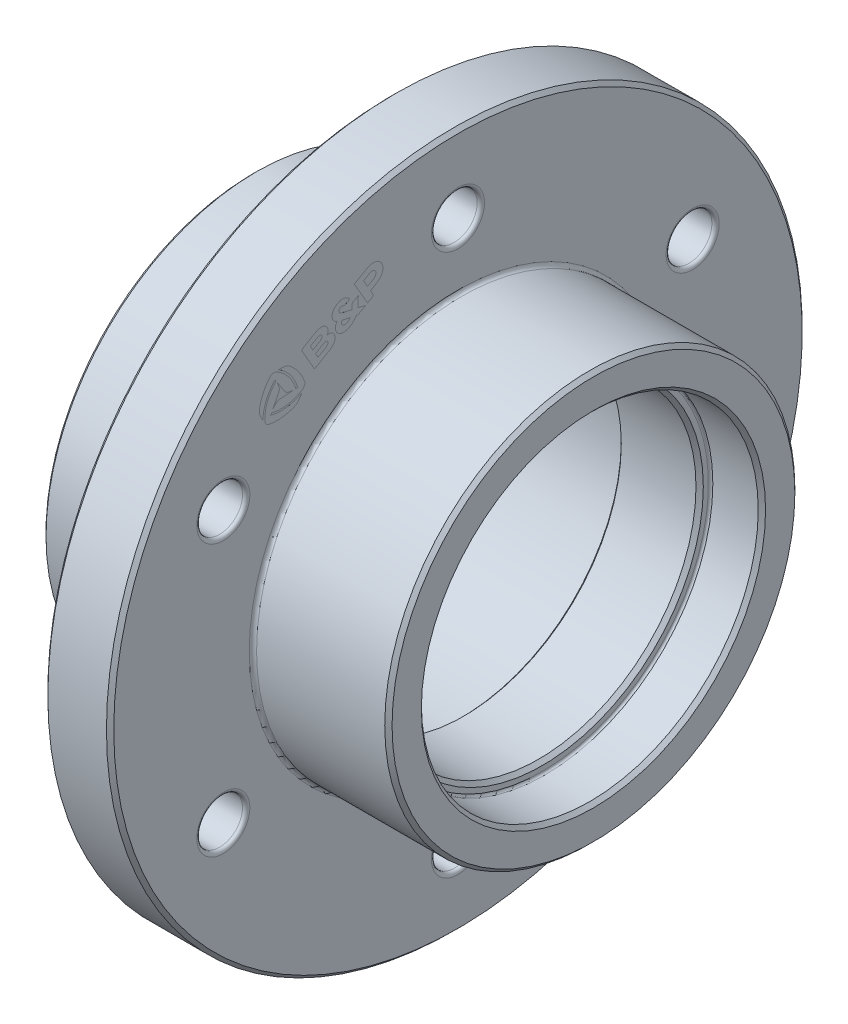
SolidWorks part; units mm, degrees
ref_plane "Alzado" through (0, 0, 0) normal (0, 0, 1) x (1, 0, 0)
ref_plane "Planta" through (0, 0, 0) normal (0, 1, 0) x (1, 0, 0)
ref_plane "Vista lateral" through (0, 0, 0) normal (1, 0, 0) x (0, 0, -1)
sketch "Croquis1" plane through (0, 0, 0) normal (0, 0, 1) x (1, 0, 0)
  line L0 (0, 0) -> (56.1633, 0) construction
  line L1 (0, 23.5) -> (0, 28.75)
  line L2 (0, 28.75) -> (7.75, 28.75)
  line L3 (8, 29) -> (18, 29)
  line L4 (19, 30) -> (19, 47.5)
  line L5 (19, 47.5) -> (28, 47.5)
  line L6 (28, 47.5) -> (28, 28.5)
  line L7 (28.5, 28) -> (46.5, 28)
  line L8 (46.5, 28) -> (46.5, 23.5)
  line L9 (0, 23.5) -> (4.6, 23.5)
  line L10 (4.6, 23.5) -> (4.6, 24.75)
  line L11 (4.6, 24.75) -> (6.7, 24.75)
  line L12 (6.7, 24.75) -> (6.7, 23.5)
  line L13 (6.7, 23.5) -> (27.5, 23.5)
  line L20 (28.5, 22.5) -> (28.5, 21.5)
  line L21 (28.5, 21.5) -> (39, 21.5)
  line L22 (8, 29) -> (7.75, 28.75)
  line L23 (46, 23) -> (39.8, 23)
  line L24 (39.5, 22.7) -> (39.5, 22)
  line L25 (46.5, 23.5) -> (46, 23)
  line L26 (39.5, 22) -> (39, 21.5)
  arc A5 (19, 30) -> (18, 29) centre (18, 30) cw
  arc A8 (27.5, 23.5) -> (28.5, 22.5) centre (27.5, 22.5) cw
  arc A9 (28, 28.5) -> (28.5, 28) centre (28.5, 28.5) ccw
  arc A10 (39.8, 23) -> (39.5, 22.7) centre (39.8, 22.7) ccw
  point P6 (46.5, 23)
  point P14 (39.5, 21.5)
  dimension "D7" = 23.5
  dimension "D5" = 1
  dimension "D8" = 8
  dimension "D11" = 57.5
  dimension "D13" = 0.5
  dimension "D18" = 43
  dimension "D16" = 1
  dimension "D22" = 0.3
  dimension "D2" = 19
  dimension "D3" = 28
  dimension "D4" = 46.5
  dimension "D6" = 58
  dimension "D9" = 47.5
  dimension "D10" = 28
  dimension "D12" = 24.75
  dimension "D14" = 2.1
  dimension "D15" = 21.8
  dimension "D17" = 18
  dimension "D19" = 7
  dimension "D20" = 45
  dimension "D21" = 46
revolve "Revolución1" add sketch "Croquis1" angle 360 about L0
sketch "Croquis2" plane through (0, 0, 0) normal (1, 0, 0) x (0, 0, -1)
  line L0 (0, 0) -> (0, 37) construction
  circle A0 centre (0, 0) radius 37 construction
  circle A1 centre (0, 37) radius 3.125
  circle A2 centre (32.0429, 18.5) radius 3.125
  circle A3 centre (32.0429, -18.5) radius 3.125
  circle A4 centre (0, -37) radius 3.125
  circle A5 centre (-32.0429, -18.5) radius 3.125
  circle A6 centre (-32.0429, 18.5) radius 3.125
  point P18 (0, 0)
  dimension "D1" = 6.25
  dimension "D2" = 74
  dimension "D3" = 6
extrude "Cortar-Extruir2" cut sketch "Croquis2" along normal through all
chamfer "Chaflán1" distance 0.5 angle 45 4 edges at (28, 0, 47.5) (19, 0, 47.5) (46.5, 0, 28) (0, 0, 28.75)
fillet "Redondeo2" radius 0.5 12 edges at (19, 18.5, -35.1679) (28, 18.5, -28.9179) (19, -18.5, -35.1679) (28, -18.5, -28.9179) (19, -37, -3.125) (28, -37, 3.125) (19, -18.5, 28.9179) (28, -18.5, 35.1679) (19, 18.5, 28.9179) (28, 18.5, 35.1679) (19, 37, -3.125) (28, 37, 3.125)
chamfer "Chaflán2" distance 0.3 angle 45 1 edges at (28.5, 0, 21.5)
chamfer "Chaflán3" distance 1 angle 45 1 edges at (0, 0, 23.5)
sketch "Croquis3" plane through (28, 0, 0) normal (1, 0, 0) x (0, 0, -1)
  line L0 (0, 0) -> (0, 37) construction
  line L1 (0, 0) -> (-32.0429, 18.5) construction
  line L2 (-12.5294, 37.1945) -> (-14.1517, 36.2579)
  line L3 (-14.1517, 36.2579) -> (-12.3456, 33.1298)
  line L4 (-12.3456, 33.1298) -> (-11.7225, 33.4895)
  line L5 (-11.6274, 33.8445) -> (-11.9408, 34.3873)
  line L6 (-11.9408, 34.3873) -> (-11.2369, 34.7937)
  line L7 (-11.5941, 35.5282) -> (-12.3482, 35.0929)
  line L8 (-12.3482, 35.0929) -> (-12.8933, 36.0372)
  line L9 (-12.8933, 36.0372) -> (-12.1393, 36.4725)
  line L10 (-13.6737, 33.2278) -> (-13.6701, 33.2681)
  line L11 (-13.6701, 33.2681) -> (-13.609, 34.6574)
  line L12 (-13.609, 34.6574) -> (-14.3198, 34.247)
  line L13 (-14.4494, 34.0353) -> (-14.4814, 33.4099)
  line L14 (-14.4814, 33.4099) -> (-15.3436, 33.6051)
  line L15 (-15.4143, 34.4672) -> (-14.7923, 34.8263)
  line L16 (-14.7923, 34.8263) -> (-14.8004, 34.8363)
  line L17 (-13.886, 32.425) -> (-13.7462, 32.3965)
  line L18 (-13.5644, 32.4261) -> (-12.5979, 32.9841)
  line L19 (-12.5979, 32.9841) -> (-13.6737, 33.2278)
  line L20 (-15.8109, 32.8267) -> (-14.7061, 32.5936)
  line L21 (-19.5117, 33.1633) -> (-21.1631, 32.2098)
  line L22 (-21.2582, 31.8549) -> (-19.5821, 28.9518)
  line L23 (-19.5821, 28.9518) -> (-17.6053, 30.0931)
  line L24 (-18.9126, 31.8242) -> (-19.8104, 31.3059)
  line L25 (-19.8104, 31.3059) -> (-20.1601, 31.9117)
  line L26 (-20.1601, 31.9117) -> (-19.2623, 32.43)
  line L27 (-18.1011, 30.6968) -> (-19.1193, 30.109)
  line L28 (-19.1193, 30.109) -> (-19.4552, 30.6909)
  line L29 (-19.4552, 30.6909) -> (-18.422, 31.2874)
  line L30 (-21.8943, 27.9067) -> (-22.1419, 27.8926)
  line L31 (-24.9798, 30.3675) -> (-24.8439, 30.1601)
  line L32 (-25.5683, 26.4649) -> (-25.4565, 26.6866)
  line L33 (-24.8923, 27.473) -> (-25.3244, 26.9485)
  line L34 (-25.3244, 26.9485) -> (-24.4807, 28.6211)
  line L35 (-24.4449, 29.2781) -> (-24.683, 29.9146)
  line L36 (-24.683, 29.9146) -> (-23.6563, 28.3476)
  line L37 (-23.1053, 27.9881) -> (-22.435, 27.8761)
  line L38 (-22.435, 27.8761) -> (-24.3054, 27.7704)
  arc A0 (0, 37) -> (-32.0429, 18.5) centre (0, 0) ccw construction
  spline S0 degree 3 poles (-10.9375, 37.3698) (-11.1564, 37.4796) (-11.4054, 37.5209) (-11.6776, 37.4924) knots 1 1 1 1 2 2 2 2
  spline S1 degree 3 poles (-11.6776, 37.4924) (-11.9499, 37.4639) (-12.2365, 37.3636) (-12.5294, 37.1945) knots 2 2 2 2 3 3 3 3
  spline S2 degree 3 poles (-11.7225, 33.4895) (-11.5984, 33.5612) (-11.5557, 33.7204) (-11.6274, 33.8445) knots 6 6 6 6 7 7 7 7
  spline S3 degree 3 poles (-11.2369, 34.7937) (-10.9305, 34.9706) (-10.6887, 35.1776) (-10.5181, 35.4089) knots 9 9 9 9 10 10 10 10
  spline S4 degree 3 poles (-10.5181, 35.4089) (-10.3475, 35.6402) (-10.2531, 35.8862) (-10.2375, 36.1399) knots 10 10 10 10 11 11 11 11
  spline S5 degree 3 poles (-10.2375, 36.1399) (-10.2299, 36.2639) (-10.2632, 36.6055) (-10.4151, 36.8699) knots 11 11 11 11 12 12 12 12
  spline S6 degree 3 poles (-10.4151, 36.8699) (-10.5716, 37.1423) (-10.8517, 37.3267) (-10.9375, 37.3698) knots 12 12 12 12 13 13 13 13
  spline S7 degree 3 poles (-11.2131, 36.2509) (-11.1849, 36.1445) (-11.1897, 36.0368) (-11.2276, 35.9306) knots 0 0 0 0 1 1 1 1
  spline S8 degree 3 poles (-11.2276, 35.9306) (-11.2844, 35.7712) (-11.4077, 35.6359) (-11.5941, 35.5282) knots 1 1 1 1 2 2 2 2
  spline S9 degree 3 poles (-12.1393, 36.4725) (-11.9529, 36.5802) (-11.7768, 36.6241) (-11.6158, 36.6031) knots 5 5 5 5 6 6 6 6
  spline S10 degree 3 poles (-11.6158, 36.6031) (-11.5124, 36.5896) (-11.4235, 36.5496) (-11.3514, 36.4841) knots 6 6 6 6 7 7 7 7
  spline S11 degree 3 poles (-11.3514, 36.4841) (-11.2855, 36.4243) (-11.2377, 36.3436) (-11.2131, 36.2509) knots 7 7 7 7 8 8 8 8
  spline S12 degree 3 poles (-14.3198, 34.247) (-14.3964, 34.2028) (-14.4448, 34.1236) (-14.4494, 34.0353) knots 3 3 3 3 4 4 4 4
  spline S13 degree 3 poles (-15.3436, 33.6051) (-15.6339, 33.6695) (-15.8393, 33.723) (-15.9541, 33.7643) knots 6 6 6 6 7 7 7 7
  spline S14 degree 3 poles (-15.9541, 33.7643) (-16.069, 33.8056) (-16.1531, 33.8714) (-16.2043, 33.96) knots 7 7 7 7 8 8 8 8
  spline S15 degree 3 poles (-16.2043, 33.96) (-16.2573, 34.0518) (-16.2691, 34.1444) (-16.2394, 34.2353) knots 8 8 8 8 9 9 9 9
  spline S16 degree 3 poles (-16.2394, 34.2353) (-16.2098, 34.3263) (-16.1475, 34.3997) (-16.0543, 34.4535) knots 9 9 9 9 10 10 10 10
  spline S17 degree 3 poles (-16.0543, 34.4535) (-15.9578, 34.5093) (-15.8581, 34.524) (-15.7583, 34.4973) knots 10 10 10 10 11 11 11 11
  spline S18 degree 3 poles (-15.7583, 34.4973) (-15.7286, 34.4893) (-15.6994, 34.4773) (-15.6714, 34.4617) knots 11 11 11 11 12 12 12 12
  spline S19 degree 3 poles (-15.6714, 34.4617) (-15.5938, 34.4184) (-15.4952, 34.4205) (-15.4143, 34.4672) knots 12 12 12 12 13 13 13 13
  spline S20 degree 3 poles (-14.8004, 34.8363) (-14.9946, 35.0763) (-15.2293, 35.2278) (-15.4979, 35.2865) knots 15 15 15 15 16 16 16 16
  spline S21 degree 3 poles (-15.4979, 35.2865) (-15.8028, 35.353) (-16.1262, 35.2893) (-16.4592, 35.097) knots 16 16 16 16 17 17 17 17
  spline S22 degree 3 poles (-16.4592, 35.097) (-16.6856, 34.9663) (-16.8628, 34.8073) (-16.986, 34.6244) knots 17 17 17 17 18 18 18 18
  spline S23 degree 3 poles (-16.986, 34.6244) (-17.1091, 34.4415) (-17.178, 34.2488) (-17.1907, 34.0517) knots 18 18 18 18 19 19 19 19
  spline S24 degree 3 poles (-17.1907, 34.0517) (-17.2034, 33.8545) (-17.1589, 33.6663) (-17.0585, 33.4923) knots 19 19 19 19 20 20 20 20
  spline S25 degree 3 poles (-17.0585, 33.4923) (-16.9488, 33.3024) (-16.7694, 33.1514) (-16.5252, 33.0437) knots 20 20 20 20 21 21 21 21
  spline S26 degree 3 poles (-16.5252, 33.0437) (-16.6487, 32.8499) (-16.722, 32.6493) (-16.743, 32.4475) knots 21 21 21 21 22 22 22 22
  spline S27 degree 3 poles (-16.743, 32.4475) (-16.7641, 32.2456) (-16.7192, 32.0469) (-16.6096, 31.857) knots 22 22 22 22 23 23 23 23
  spline S28 degree 3 poles (-16.6096, 31.857) (-16.4944, 31.6576) (-16.3371, 31.5099) (-16.142, 31.4181) knots 23 23 23 23 24 24 24 24
  spline S29 degree 3 poles (-16.142, 31.4181) (-15.9469, 31.3262) (-15.7233, 31.2938) (-15.4775, 31.3218) knots 24 24 24 24 25 25 25 25
  spline S30 degree 3 poles (-15.4775, 31.3218) (-15.2317, 31.3499) (-14.9771, 31.4391) (-14.7206, 31.5872) knots 25 25 25 25 26 26 26 26
  spline S31 degree 3 poles (-14.7206, 31.5872) (-14.3376, 31.8084) (-14.0568, 32.0902) (-13.886, 32.425) knots 26 26 26 26 27 27 27 27
  spline S32 degree 3 poles (-13.7462, 32.3965) (-13.684, 32.3838) (-13.6194, 32.3944) (-13.5644, 32.4261) knots 29 29 29 29 30 30 30 30
  spline S33 degree 3 poles (-14.7061, 32.5936) (-14.8076, 32.4464) (-14.9317, 32.3299) (-15.0749, 32.2472) knots 0 0 0 0 1 1 1 1
  spline S34 degree 3 poles (-15.0749, 32.2472) (-15.2248, 32.1606) (-15.3767, 32.1254) (-15.5263, 32.1424) knots 1 1 1 1 2 2 2 2
  spline S35 degree 3 poles (-15.5263, 32.1424) (-15.6759, 32.1593) (-15.7842, 32.224) (-15.8482, 32.3348) knots 2 2 2 2 3 3 3 3
  spline S36 degree 3 poles (-15.8482, 32.3348) (-15.8902, 32.4075) (-15.9071, 32.4876) (-15.8985, 32.5727) knots 3 3 3 3 4 4 4 4
  spline S37 degree 3 poles (-15.8985, 32.5727) (-15.89, 32.6578) (-15.8605, 32.7432) (-15.8109, 32.8267) knots 4 4 4 4 5 5 5 5
  spline S38 degree 3 poles (-16.9705, 31.806) (-17.0605, 31.9247) (-17.176, 32.0142) (-17.314, 32.0721) knots 0 0 0 0 1 1 1 1
  spline S39 degree 3 poles (-17.314, 32.0721) (-17.4812, 32.1422) (-17.6811, 32.1426) (-17.8923, 32.0732) knots 1 1 1 1 2 2 2 2
  spline S40 degree 3 poles (-17.8923, 32.0732) (-17.6579, 32.4176) (-17.6726, 32.6513) (-17.839, 32.9783) knots 2 2 2 2 3 3 3 3
  spline S41 degree 3 poles (-17.839, 32.9783) (-17.9924, 33.244) (-18.2198, 33.3961) (-18.5149, 33.4304) knots 3 3 3 3 4 4 4 4
  spline S42 degree 3 poles (-18.5149, 33.4304) (-18.8101, 33.4646) (-19.1455, 33.3747) (-19.5117, 33.1633) knots 4 4 4 4 5 5 5 5
  spline S43 degree 3 poles (-21.1631, 32.2098) (-21.2872, 32.1382) (-21.3299, 31.979) (-21.2582, 31.8549) knots 6 6 6 6 7 7 7 7
  spline S44 degree 3 poles (-17.6053, 30.0931) (-17.2289, 30.3103) (-16.9753, 30.567) (-16.8512, 30.8559) knots 9 9 9 9 10 10 10 10
  spline S45 degree 3 poles (-16.8512, 30.8559) (-16.7271, 31.1448) (-16.7439, 31.4292) (-16.901, 31.7012) knots 10 10 10 10 11 11 11 11
  spline S46 degree 3 poles (-16.901, 31.7012) (-16.9219, 31.7375) (-16.9453, 31.7727) (-16.9705, 31.806) knots 11 11 11 11 12 12 12 12
  spline S47 degree 3 poles (-18.5715, 32.306) (-18.5655, 32.2469) (-18.5759, 32.1868) (-18.6024, 32.1273) knots 0 0 0 0 1 1 1 1
  spline S48 degree 3 poles (-18.6024, 32.1273) (-18.6517, 32.0166) (-18.7561, 31.9146) (-18.9126, 31.8242) knots 1 1 1 1 2 2 2 2
  spline S49 degree 3 poles (-19.2623, 32.43) (-19.0992, 32.5241) (-18.9594, 32.5685) (-18.8466, 32.5619) knots 5 5 5 5 6 6 6 6
  spline S50 degree 3 poles (-18.8466, 32.5619) (-18.7883, 32.5584) (-18.7363, 32.5417) (-18.6922, 32.5122) knots 6 6 6 6 7 7 7 7
  spline S51 degree 3 poles (-18.6922, 32.5122) (-18.6252, 32.4674) (-18.5801, 32.3903) (-18.5715, 32.306) knots 7 7 7 7 8 8 8 8
  spline S52 degree 3 poles (-17.8533, 31.3697) (-17.7966, 31.3302) (-17.7586, 31.266) (-17.7491, 31.1936) knots 0 0 0 0 1 1 1 1
  spline S53 degree 3 poles (-17.7491, 31.1936) (-17.7412, 31.1329) (-17.7511, 31.0701) (-17.7783, 31.0072) knots 1 1 1 1 2 2 2 2
  spline S54 degree 3 poles (-17.7783, 31.0072) (-17.826, 30.8974) (-17.9346, 30.793) (-18.1011, 30.6968) knots 2 2 2 2 3 3 3 3
  spline S55 degree 3 poles (-18.422, 31.2874) (-18.2656, 31.3777) (-18.1292, 31.4223) (-18.0166, 31.4198) knots 6 6 6 6 7 7 7 7
  spline S56 degree 3 poles (-18.0166, 31.4198) (-17.9539, 31.4183) (-17.899, 31.4014) (-17.8533, 31.3697) knots 7 7 7 7 8 8 8 8
  spline S57 degree 3 poles (-23.0974, 31.0717) (-23.2394, 31.175) (-23.4049, 31.2412) (-23.5786, 31.2666) knots 0 0 0 0 1 1 1 1
  spline S58 degree 3 poles (-23.5786, 31.2666) (-23.8877, 31.3119) (-24.2014, 31.3318) (-24.5167, 31.3253) knots 1 1 1 1 2 2 2 2
  spline S59 degree 3 poles (-24.5167, 31.3253) (-24.2025, 31.1391) (-23.9063, 30.9232) (-23.6304, 30.6787) knots 2 2 2 2 3 3 3 3
  spline S60 degree 3 poles (-23.6304, 30.6787) (-23.0493, 30.164) (-22.5835, 29.5449) (-22.2461, 28.8387) knots 3 3 3 3 4 4 4 4
  spline S61 degree 3 poles (-22.2461, 28.8387) (-22.1013, 28.5357) (-21.984, 28.2245) (-21.8943, 27.9067) knots 4 4 4 4 5 5 5 5
  spline S62 degree 3 poles (-22.1419, 27.8926) (-22.2249, 28.1772) (-22.3318, 28.4587) (-22.4637, 28.7347) knots 6 6 6 6 7 7 7 7
  spline S63 degree 3 poles (-22.4637, 28.7347) (-23.0011, 29.8595) (-23.8701, 30.721) (-24.8981, 31.2585) knots 7 7 7 7 8 8 8 8
  spline S64 degree 3 poles (-24.8981, 31.2585) (-24.9471, 31.2841) (-25.0027, 31.2944) (-25.0577, 31.2879) knots 8 8 8 8 9 9 9 9
  spline S65 degree 3 poles (-25.0577, 31.2879) (-25.1861, 31.2729) (-25.3145, 31.2533) (-25.4426, 31.2292) knots 9 9 9 9 10 10 10 10
  spline S66 degree 3 poles (-25.4426, 31.2292) (-25.5013, 31.2181) (-25.5548, 31.1881) (-25.5949, 31.1438) knots 10 10 10 10 11 11 11 11
  spline S67 degree 3 poles (-25.5949, 31.1438) (-25.7654, 30.9551) (-25.926, 30.7535) (-26.075, 30.5392) knots 11 11 11 11 12 12 12 12
  spline S68 degree 3 poles (-26.075, 30.5392) (-26.6735, 29.6787) (-27.0162, 28.7166) (-27.1193, 27.7431) knots 12 12 12 12 13 13 13 13
  spline S69 degree 3 poles (-27.1193, 27.7431) (-27.1378, 27.5685) (-27.1123, 27.3921) (-27.0475, 27.2289) knots 13 13 13 13 14 14 14 14
  spline S70 degree 3 poles (-27.0475, 27.2289) (-26.9322, 26.9386) (-26.7926, 26.6569) (-26.6293, 26.3872) knots 14 14 14 14 15 15 15 15
  spline S71 degree 3 poles (-26.6293, 26.3872) (-26.6251, 26.7524) (-26.5862, 27.1168) (-26.5125, 27.478) knots 15 15 15 15 16 16 16 16
  spline S72 degree 3 poles (-26.5125, 27.478) (-26.3573, 28.2386) (-26.054, 28.9515) (-25.6111, 29.5969) knots 16 16 16 16 17 17 17 17
  spline S73 degree 3 poles (-25.6111, 29.5969) (-25.4211, 29.8737) (-25.2102, 30.1309) (-24.9798, 30.3675) knots 17 17 17 17 18 18 18 18
  spline S74 degree 3 poles (-24.8439, 30.1601) (-25.0488, 29.9459) (-25.2392, 29.7126) (-25.4123, 29.4604) knots 19 19 19 19 20 20 20 20
  spline S75 degree 3 poles (-25.4123, 29.4604) (-26.1176, 28.4326) (-26.4292, 27.2492) (-26.3807, 26.0903) knots 20 20 20 20 21 21 21 21
  spline S76 degree 3 poles (-26.3807, 26.0903) (-26.3784, 26.035) (-26.3595, 25.9817) (-26.3264, 25.9374) knots 21 21 21 21 22 22 22 22
  spline S77 degree 3 poles (-26.3264, 25.9374) (-26.2492, 25.8336) (-26.168, 25.7322) (-26.0831, 25.6333) knots 22 22 22 22 23 23 23 23
  spline S78 degree 3 poles (-26.0831, 25.6333) (-26.0442, 25.588) (-25.9914, 25.5567) (-25.933, 25.5442) knots 23 23 23 23 24 24 24 24
  spline S79 degree 3 poles (-25.933, 25.5442) (-25.6844, 25.4908) (-25.4295, 25.4526) (-25.1693, 25.4306) knots 24 24 24 24 25 25 25 25
  spline S80 degree 3 poles (-25.1693, 25.4306) (-24.1249, 25.3426) (-23.1204, 25.5269) (-22.2257, 25.9244) knots 25 25 25 25 26 26 26 26
  spline S81 degree 3 poles (-22.2257, 25.9244) (-22.0653, 25.9956) (-21.9252, 26.1059) (-21.8163, 26.2436) knots 26 26 26 26 27 27 27 27
  spline S82 degree 3 poles (-21.8163, 26.2436) (-21.6226, 26.4886) (-21.4484, 26.7504) (-21.2965, 27.0266) knots 27 27 27 27 28 28 28 28
  spline S83 degree 3 poles (-21.2965, 27.0266) (-21.6148, 26.8477) (-21.9499, 26.6991) (-22.2995, 26.5823) knots 28 28 28 28 29 29 29 29
  spline S84 degree 3 poles (-22.2995, 26.5823) (-23.0359, 26.3365) (-23.8049, 26.2427) (-24.5853, 26.3035) knots 29 29 29 29 30 30 30 30
  spline S85 degree 3 poles (-24.5853, 26.3035) (-24.92, 26.3297) (-25.2482, 26.3837) (-25.5683, 26.4649) knots 30 30 30 30 31 31 31 31
  spline S86 degree 3 poles (-25.4565, 26.6866) (-25.1685, 26.6162) (-24.8714, 26.5678) (-24.5665, 26.544) knots 32 32 32 32 33 33 33 33
  spline S87 degree 3 poles (-24.5665, 26.544) (-23.3237, 26.447) (-22.143, 26.7689) (-21.1636, 27.3904) knots 33 33 33 33 34 34 34 34
  spline S88 degree 3 poles (-21.1636, 27.3904) (-21.1169, 27.42) (-21.0802, 27.463) (-21.0583, 27.5138) knots 34 34 34 34 35 35 35 35
  spline S89 degree 3 poles (-21.0583, 27.5138) (-21.0072, 27.6325) (-20.9599, 27.7534) (-20.9168, 27.8764) knots 35 35 35 35 36 36 36 36
  spline S90 degree 3 poles (-20.9168, 27.8764) (-20.897, 27.9328) (-20.8961, 27.9942) (-20.9145, 28.0511) knots 36 36 36 36 37 37 37 37
  spline S91 degree 3 poles (-20.9145, 28.0511) (-20.9926, 28.2932) (-21.087, 28.5331) (-21.1981, 28.7693) knots 37 37 37 37 38 38 38 38
  spline S92 degree 3 poles (-21.1981, 28.7693) (-21.644, 29.7178) (-22.3059, 30.4956) (-23.0974, 31.0717) knots 38 38 38 38 39 39 39 39
  spline S93 degree 3 poles (-24.3054, 27.7704) (-24.5339, 27.7574) (-24.7467, 27.6496) (-24.8923, 27.473) knots 0 0 0 0 1 1 1 1
  spline S94 degree 3 poles (-24.4807, 28.6211) (-24.3776, 28.8255) (-24.3646, 29.0637) (-24.4449, 29.2781) knots 3 3 3 3 4 4 4 4
  spline S95 degree 3 poles (-23.6563, 28.3476) (-23.5308, 28.1561) (-23.3311, 28.0258) (-23.1053, 27.9881) knots 6 6 6 6 7 7 7 7
extrude "Cortar-Extruir3" cut sketch "Croquis3" against normal blind 0.0001
